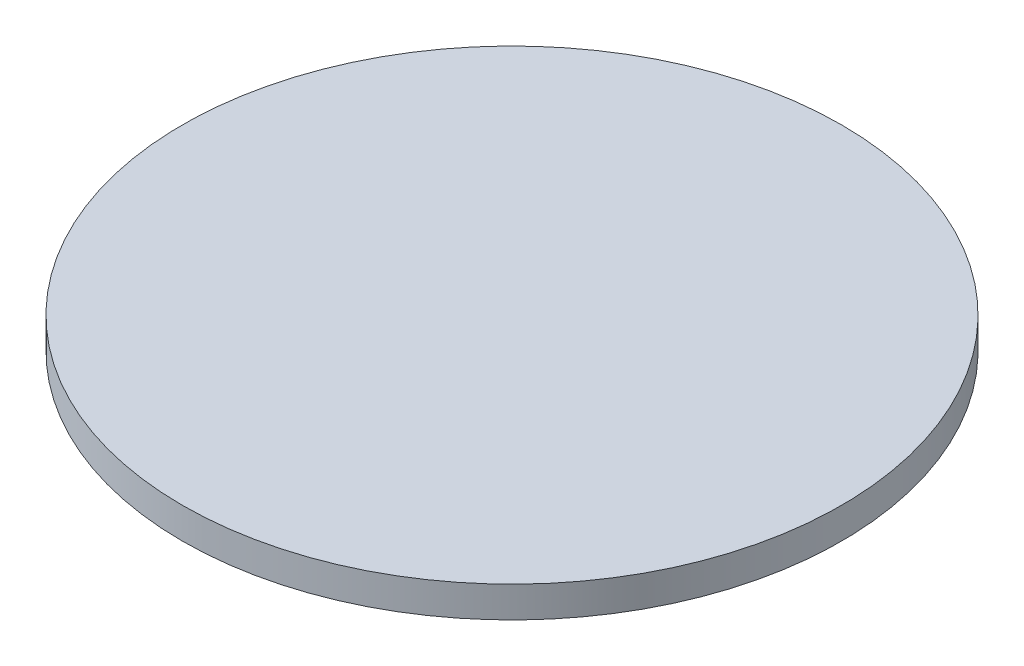
SolidWorks part; units mm, degrees
ref_plane "Front Plane" through (0, 0, 0) normal (0, 0, 1) x (1, 0, 0)
ref_plane "Top Plane" through (0, 0, 0) normal (0, 1, 0) x (1, 0, 0)
ref_plane "Right Plane" through (0, 0, 0) normal (1, 0, 0) x (0, 0, -1)
sketch "Sketch1" plane through (0, 0, 0) normal (0, 1, 0) x (1, 0, 0)
  circle A0 centre (0, 0) radius 42.5
  dimension "D1" = 85
extrude "Boss-Extrude1" add sketch "Sketch1" along normal blind 4
